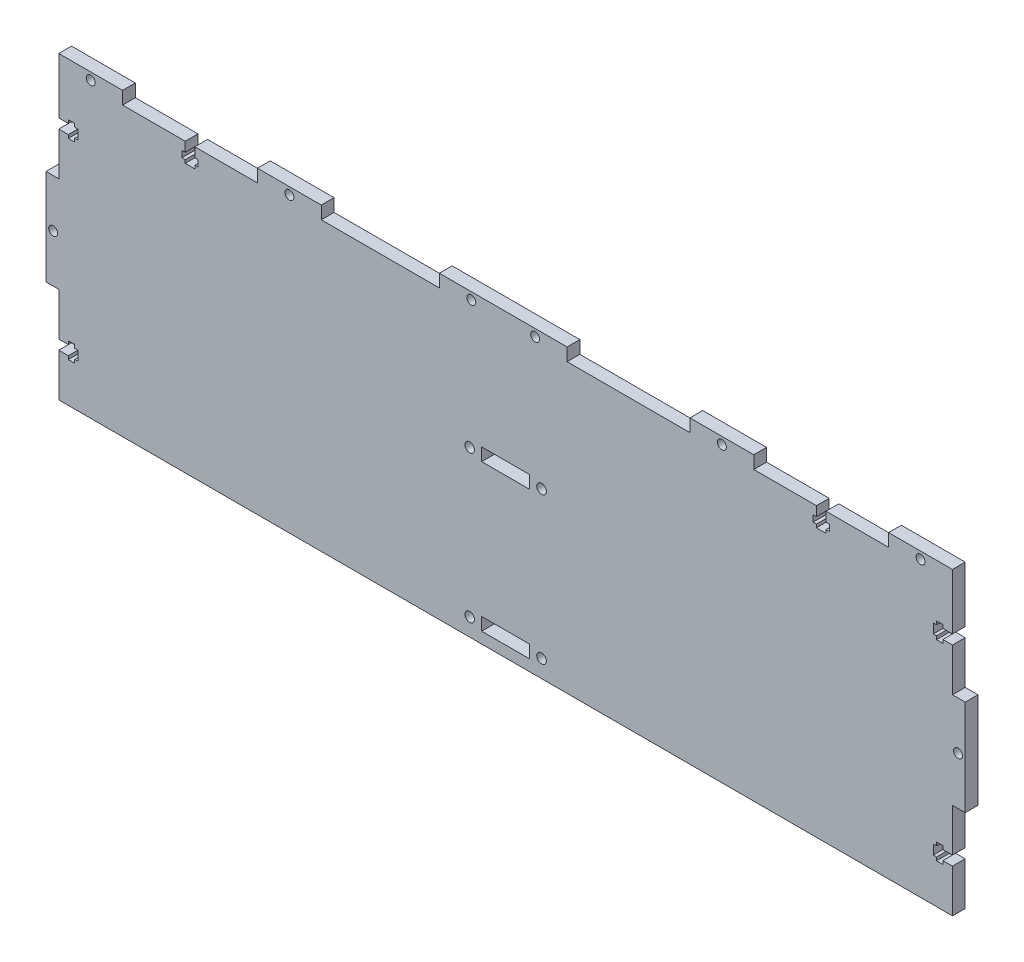
SolidWorks part; units mm, degrees
ref_plane "Спереди" through (0, 0, 0) normal (0, 0, 1) x (1, 0, 0)
ref_plane "Сверху" through (0, 0, 0) normal (0, 1, 0) x (1, 0, 0)
ref_plane "Справа" through (0, 0, 0) normal (1, 0, 0) x (0, 0, -1)
sketch "Эскиз1" plane through (0, 0, 0) normal (0, 0, 1) x (1, 0, 0)
  line L0 (81.5, 40.25) -> (77, 35.75)
  line L1 (-140, -45) -> (140, -45)
  line L2 (-140, -45) -> (-140, 45)
  line L3 (-140, 45) -> (140, 45)
  line L4 (140, -45) -> (140, 45)
  line L5 (-140, -45) -> (140, 45) construction
  line L6 (-140, 45) -> (140, -45) construction
  line L7 (-7.5, -37.5) -> (7.5, -37.5)
  line L8 (-7.5, -37.5) -> (-7.5, -41.5)
  line L9 (-7.5, -41.5) -> (7.5, -41.5)
  line L10 (7.5, -37.5) -> (7.5, -41.5)
  line L11 (-7.5, -37.5) -> (7.5, -41.5) construction
  line L12 (-7.5, -41.5) -> (7.5, -37.5) construction
  line L13 (-7.5, 4.5) -> (7.5, 4.5)
  line L14 (-7.5, 4.5) -> (-7.5, 8.5)
  line L15 (-7.5, 8.5) -> (7.5, 8.5)
  line L16 (7.5, 4.5) -> (7.5, 8.5)
  line L17 (-7.5, 4.5) -> (7.5, 8.5) construction
  line L18 (-7.5, 8.5) -> (7.5, 4.5) construction
  line L19 (-10, -33.25) -> (10, -33.25)
  line L20 (-10, -33.25) -> (-10, -2.75)
  line L21 (-10, -2.75) -> (10, -2.75)
  line L22 (10, -33.25) -> (10, -2.75)
  line L23 (-10, -33.25) -> (10, -2.75) construction
  line L24 (-10, -2.75) -> (10, -33.25) construction
  line L25 (115, -2.25) -> (81.5, -2.25)
  line L26 (119.5, 2.25) -> (119.5, 35.75)
  line L27 (115, 40.25) -> (81.5, 40.25)
  line L28 (77, 2.25) -> (77, 35.75)
  line L29 (119.5, -2.25) -> (77, 40.25) construction
  line L30 (119.5, 40.25) -> (77, -2.25) construction
  line L31 (119.5, 35.75) -> (115, 40.25)
  line L32 (119.5, 2.25) -> (115, -2.25)
  line L33 (81.5, -2.25) -> (77, 2.25)
  line L118 (77, 28) -> (67, 28)
  line L119 (0, -31.3693) -> (0, 31.3693) construction
  line L120 (67, 28) -> (67, 10)
  line L121 (67, 10) -> (77, 10)
  line L123 (119.5, 28) -> (129.5, 28)
  line L124 (119.5, 28) -> (119.5, 10)
  line L125 (119.5, 10) -> (129.5, 10)
  line L126 (129.5, 28) -> (129.5, 10)
  line L128 (89.25, -2.25) -> (107.25, -2.25)
  line L129 (89.25, -2.25) -> (89.25, -12.25)
  line L130 (89.25, -12.25) -> (107.25, -12.25)
  line L131 (107.25, -2.25) -> (107.25, -12.25)
  circle A0 centre (11.25, 6.5) radius 1.5
  circle A1 centre (-11.25, 6.5) radius 1.5
  circle A2 centre (-11.25, -39.5) radius 1.5
  circle A3 centre (11.25, -39.5) radius 1.5
  point P0 (0, 0)
  point P6 (0, -39.5)
  point P12 (0, 6.5)
  point P17 (0, -18)
  point P33 (98.25, 19)
  point P49 (67, 19)
  point P51 (77, 19)
  point P56 (129.5, 19)
  point P61 (98.25, -12.25)
  dimension "D10" = 3
  dimension "D1" = 280
  dimension "D2" = 90
  dimension "D3" = 3.5
  dimension "D4" = 15
  dimension "D5" = 4
  dimension "D6" = 42
  dimension "D7" = 11.75
  dimension "D8" = 30.5
  dimension "D9" = 20
  dimension "D11" = 42.5
  dimension "D12" = 64
  dimension "D13" = 98.25
  dimension "D14" = 18
  dimension "D19" = 10
  dimension "D55" = 11.25
  dimension "D56" = 0
  dimension "D57" = 11.25
  dimension "D58" = 0
extrude "Бобышка-Вытянуть1" add sketch "Эскиз1" along normal blind 4
sketch "Эскиз2" plane through (0, 0, 0) normal (0, 0, 1) x (1, 0, 0)
  line L0 (-140, 45) -> (140, 45) construction
  line L2 (120, 45) -> (120, 49)
  line L4 (19.25, 45) -> (19.25, 49)
  line L5 (140, -45) -> (140, 45) construction
  line L7 (-140, 45) -> (140, 45) construction
  line L8 (57.75, 45) -> (77.75, 45)
  line L9 (0, -2.2) -> (0, 2.2) construction
  line L10 (57.75, 45) -> (57.75, 49)
  line L11 (57.75, 49) -> (77.75, 49)
  line L12 (77.75, 45) -> (77.75, 49)
  line L13 (-20.75, 45) -> (-20.75, 49)
  line L15 (-120, 45) -> (-120, 49)
  line L17 (-144, -45) -> (-144, -15)
  line L18 (140, 45) -> (144, 45)
  line L19 (140, 45) -> (140, 15)
  line L20 (140, 15) -> (144, 15)
  line L21 (144, 45) -> (144, 15)
  line L22 (140, -45) -> (144, -45)
  line L23 (140, -45) -> (140, -15)
  line L24 (140, -15) -> (144, -15)
  line L25 (144, -45) -> (144, -15)
  line L26 (-140, -15) -> (-144, -15)
  line L27 (-140, -45) -> (-140, -15)
  line L28 (-140, -45) -> (-144, -45)
  line L29 (-144, 45) -> (-144, 15)
  line L30 (-140, 15) -> (-144, 15)
  line L31 (-140, 45) -> (-140, 15)
  line L32 (-140, 45) -> (-144, 45)
  line L33 (-20.75, 46.75) -> (-10.75, 46.75) construction
  line L34 (-144, 15) -> (-140, 15)
  line L35 (-144, 15) -> (-144, -15)
  line L36 (-144, -15) -> (-140, -15)
  line L37 (-140, 15) -> (-140, -15)
  line L38 (-140, 45) -> (-120, 45)
  line L39 (-140, 45) -> (-140, 49)
  line L40 (-140, 49) -> (-120, 49)
  line L41 (-120, 45) -> (-120, 49)
  line L42 (-20.75, 49) -> (19.25, 49)
  line L43 (-20.75, 49) -> (-20.75, 45)
  line L44 (-20.75, 45) -> (19.25, 45)
  line L45 (19.25, 49) -> (19.25, 45)
  line L46 (120, 49) -> (140, 49)
  line L47 (120, 49) -> (120, 45)
  line L48 (120, 45) -> (140, 45)
  line L49 (140, 49) -> (140, 45)
  line L50 (144, 15) -> (140, 15)
  line L51 (144, 15) -> (144, -15)
  line L52 (144, -15) -> (140, -15)
  line L53 (140, 15) -> (140, -15)
  line L54 (-10.75, 46.75) -> (9.25, 46.75) construction
  line L55 (9.25, 46.75) -> (19.25, 46.75) construction
  line L57 (-57.75, 45) -> (-77.75, 45)
  line L58 (-57.75, 45) -> (-57.75, 49)
  line L59 (-57.75, 49) -> (-77.75, 49)
  line L60 (-77.75, 45) -> (-77.75, 49)
  circle A4 centre (141.75, 30) radius 1.4
  circle A5 centre (141.75, -30) radius 1.4
  circle A6 centre (-141.75, -30) radius 1.4
  circle A7 centre (-141.75, 30) radius 1.4
  circle A8 centre (-10.75, 46.75) radius 1.4
  circle A9 centre (9.25, 46.75) radius 1.4
  circle A10 centre (-141.75, 0) radius 1.4
  circle A11 centre (141.75, 0) radius 1.4
  circle A12 centre (-130, 46.75) radius 1.4
  circle A13 centre (130, 46.75) radius 1.4
  circle A14 centre (67.75, 46.75) radius 1.4
  circle A15 centre (-67.75, 46.75) radius 1.4
  point P42 (144, -30)
  point P44 (144, 30)
  point P63 (-130, 49)
  point P64 (-144, 0)
  point P74 (67.75, 49)
  point P77 (-67.75, 49)
  point P80 (-0.75, 49)
  dimension "D4" = 4
  dimension "D8" = 2.8
  dimension "D10" = 20
  dimension "D11" = 2.8
  dimension "D1" = 4
  dimension "D2" = 20
  dimension "D3" = 40
  dimension "D5" = 2.25
  dimension "D6" = 4
  dimension "D7" = 30
  dimension "D9" = 2.25
  dimension "D12" = 82.25
  dimension "D13" = 82.25
  dimension "D14" = 139.25
extrude "Бобышка-Вытянуть7" add sketch "Эскиз2" along normal through all contours L37 L30 L35 L26 A10 | L40 L39 L38 L15 A12 | L13 L44 L4 L42 A9 A8 | L49 L46 L2 L48 A13 | L20 L53 L24 L51 A11 | L60 L57 L58 L59 A15 | L8 L12 L11 L10 A14
sketch "Эскиз3" plane through (0, 0, 4) normal (0, 0, 1) x (1, 0, 0)
  line L0 (-120, 45) -> (-77.75, 45) construction
  line L5 (-120, 45) -> (-77.75, 45) construction
  line L6 (96.325, 42) -> (96.325, 40)
  line L7 (101.425, 40) -> (96.325, 40)
  line L20 (101.425, 42) -> (101.425, 40)
  line L21 (-100.375, 45) -> (-97.375, 45)
  line L26 (101.425, 42) -> (96.325, 42)
  line L31 (-100.375, 45) -> (-100.375, 39)
  line L56 (-100.375, 39) -> (-97.375, 39)
  line L57 (-97.375, 45) -> (-97.375, 39)
  line L59 (-101.425, 42) -> (-96.325, 42)
  line L60 (-101.425, 42) -> (-101.425, 40)
  line L61 (-101.425, 40) -> (-96.325, 40)
  line L62 (-96.325, 42) -> (-96.325, 40)
  line L70 (97.375, 45) -> (97.375, 39)
  line L71 (100.375, 39) -> (97.375, 39)
  line L72 (-53.8333, 45) -> (-20.75, 45) construction
  line L73 (-140, 15) -> (-140, 49) construction
  line L74 (-140, 31.5) -> (-134, 31.5)
  line L75 (-140, 31.5) -> (-140, 28.5)
  line L76 (-140, 28.5) -> (-134, 28.5)
  line L77 (-134, 31.5) -> (-134, 28.5)
  line L78 (-140, 45) -> (-140, 15) construction
  line L79 (-137, 32.55) -> (-135, 32.55)
  line L80 (-137, 32.55) -> (-137, 27.45)
  line L81 (-137, 27.45) -> (-135, 27.45)
  line L82 (-135, 32.55) -> (-135, 27.45)
  line L83 (-144, 0) -> (-110, 0) construction
  line L84 (-144, 15) -> (-144, -15) construction
  line L85 (-135, -32.55) -> (-135, -27.45)
  line L86 (-137, -27.45) -> (-135, -27.45)
  line L87 (-137, -32.55) -> (-137, -27.45)
  line L88 (-137, -32.55) -> (-135, -32.55)
  line L89 (-134, -31.5) -> (-134, -28.5)
  line L90 (-140, -28.5) -> (-134, -28.5)
  line L91 (-140, -31.5) -> (-140, -28.5)
  line L92 (-140, -31.5) -> (-134, -31.5)
  line L93 (0, -2.2) -> (0, 2.2) construction
  line L94 (144, 0) -> (110, 0) construction
  line L95 (140, 45) -> (140, 15) construction
  line L96 (53.8333, 45) -> (20.75, 45) construction
  line L97 (100.375, 45) -> (100.375, 39)
  line L98 (100.375, 45) -> (97.375, 45)
  line L99 (140, -31.5) -> (134, -31.5)
  line L100 (140, -31.5) -> (140, -28.5)
  line L101 (140, -28.5) -> (134, -28.5)
  line L102 (134, -31.5) -> (134, -28.5)
  line L103 (137, -32.55) -> (135, -32.55)
  line L104 (137, -32.55) -> (137, -27.45)
  line L105 (137, -27.45) -> (135, -27.45)
  line L106 (135, -32.55) -> (135, -27.45)
  line L107 (135, 32.55) -> (135, 27.45)
  line L108 (137, 27.45) -> (135, 27.45)
  line L109 (137, 32.55) -> (137, 27.45)
  line L110 (137, 32.55) -> (135, 32.55)
  line L111 (134, 31.5) -> (134, 28.5)
  line L112 (140, 28.5) -> (134, 28.5)
  line L113 (140, 31.5) -> (140, 28.5)
  line L114 (140, 31.5) -> (134, 31.5)
  point P10 (-98.875, 42)
  point P11 (-98.875, 45)
  point P34 (-135, 30)
  point P35 (-134, 30)
  point P38 (-140, 30)
  dimension "D1" = 3
  dimension "D2" = 6
  dimension "D3" = 3
  dimension "D4" = 2
  dimension "D6" = 5.1
  dimension "D8" = 6
  dimension "D10" = 3
  dimension "D7" = 3
extrude "Вырез-Вытянуть1" cut sketch "Эскиз3" against normal through all
